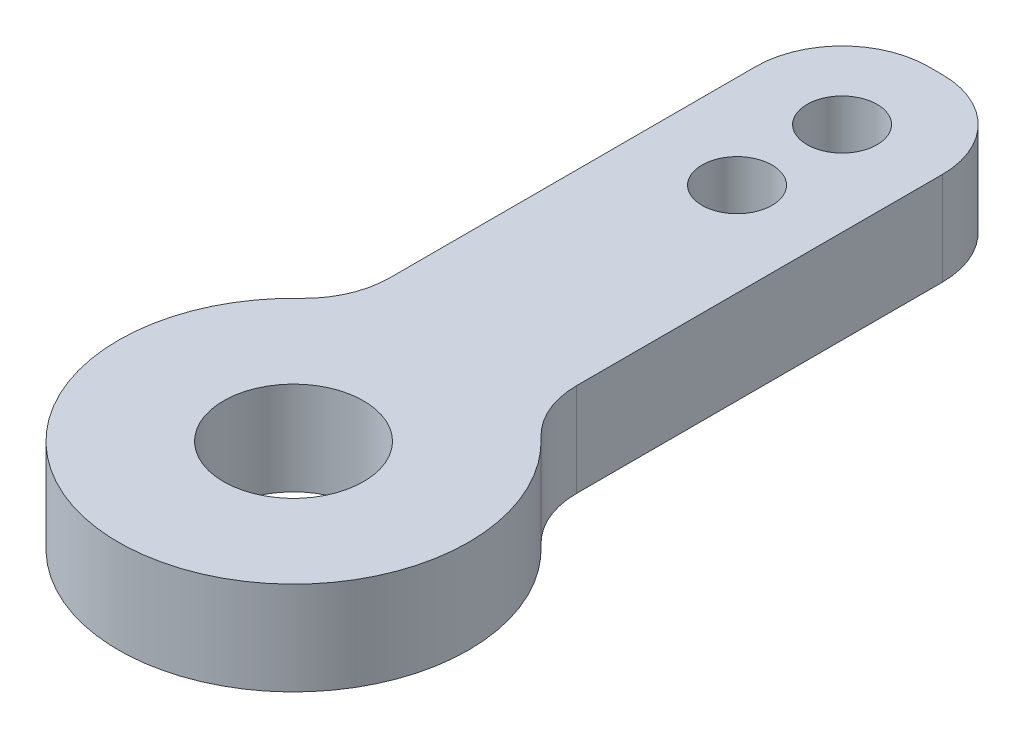
SolidWorks part; units mm, degrees
ref_plane "Front Plane" through (0, 0, 0) normal (0, 0, 1) x (1, 0, 0)
ref_plane "Top Plane" through (0, 0, 0) normal (0, 1, 0) x (1, 0, 0)
ref_plane "Right Plane" through (0, 0, 0) normal (1, 0, 0) x (0, 0, -1)
sketch "Sketch1" plane through (0, 0, 0) normal (0, 1, 0) x (1, 0, 0)
  line L0 (-4, 8.8) -> (-4, -6.8667)
  line L1 (-0.3, 12.5) -> (0.3, 12.5)
  line L7 (4, 8.8) -> (4, -6.8667)
  arc A0 (-5.1563, -9.5536) -> (5.1562, -9.5536) centre (0, -15) ccw
  circle A1 centre (0, -15) radius 3
  arc A2 (4, -6.8667) -> (5.1562, -9.5536) centre (7.7, -6.8667) ccw
  arc A3 (-4, -6.8667) -> (-5.1563, -9.5536) centre (-7.7, -6.8667) cw
  arc A4 (4, 8.8) -> (0.3, 12.5) centre (0.3, 8.8) ccw
  arc A5 (-4, 8.8) -> (-0.3, 12.5) centre (-0.3, 8.8) cw
  circle A6 centre (0, 8.5) radius 1.5
  circle A7 centre (0, 4) radius 1.5
  point P0 (0, 0)
  dimension "D5" = 6
  dimension "D6" = 3.7
  dimension "D7" = 3
  dimension "D8" = 3
  dimension "D9" = 1.5
  dimension "D10" = 2.5
  dimension "D1" = 8
  dimension "D2" = 35
  dimension "D4" = 4
  dimension "D11" = 7.5
extrude "Boss-Extrude1" add sketch "Sketch1" along normal blind 4
